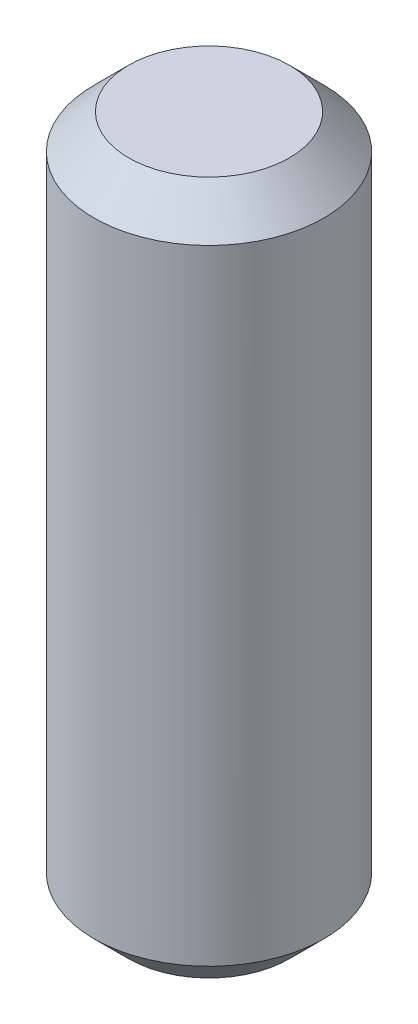
SolidWorks part; units mm, degrees
ref_plane "Front Plane" through (0, 0, 0) normal (0, 0, 1) x (1, 0, 0)
ref_plane "Top Plane" through (0, 0, 0) normal (0, 1, 0) x (1, 0, 0)
ref_plane "Right Plane" through (0, 0, 0) normal (1, 0, 0) x (0, 0, -1)
sketch "Sketch2" plane through (0, 0, 0) normal (0, 1, 0) x (1, 0, 0)
  circle A0 centre (0, 0) radius 4.975
  dimension "D1" = 9.95
extrude "Boss-Extrude1" add sketch "Sketch2" along normal blind 30
chamfer "Chamfer1" distance 1.5 angle 45 2 edges at (0, 0, 4.975) (0, 30, 4.975)
